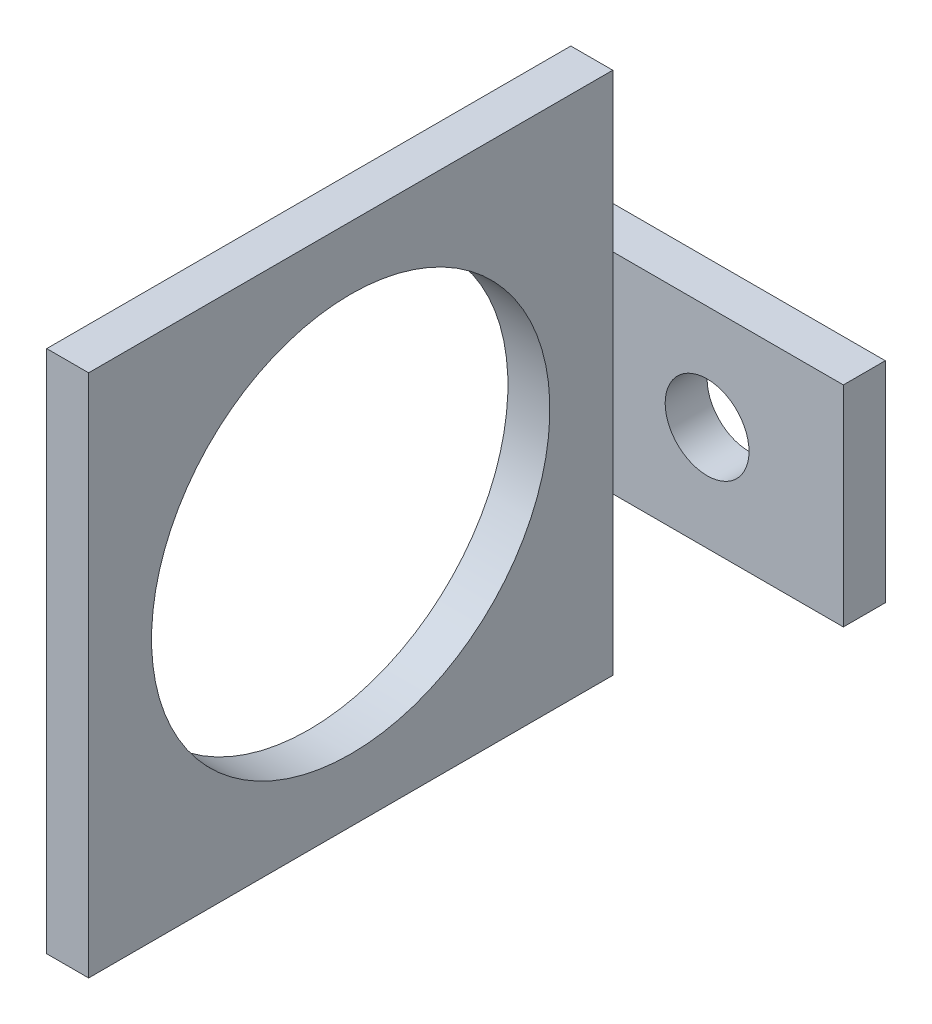
SolidWorks part; units mm, degrees
ref_plane "Front Plane" through (0, 0, 0) normal (0, 0, 1) x (1, 0, 0)
ref_plane "Top Plane" through (0, 0, 0) normal (0, 1, 0) x (1, 0, 0)
ref_plane "Right Plane" through (0, 0, 0) normal (1, 0, 0) x (0, 0, -1)
sketch "Sketch1" plane through (0, 0, 0) normal (0, 0, 1) x (1, 0, 0)
  line L1 (-6.5, 5) -> (6.5, 5)
  line L2 (-6.5, 5) -> (-6.5, -5)
  line L3 (-6.5, -5) -> (6.5, -5)
  line L4 (6.5, 5) -> (6.5, -5)
  line L5 (-6.5, 5) -> (6.5, -5) construction
  line L6 (-6.5, -5) -> (6.5, 5) construction
  point P0 (0, 0)
  dimension "D1" = 13
  dimension "D2" = 10
extrude "Boss-Extrude1" add sketch "Sketch1" along normal blind 2
sketch "Sketch2" plane through (0, 0, 2) normal (0, 0, 1) x (1, 0, 0)
  line L0 (-6.5, -5) -> (6.5, -5) construction
  line L1 (-6.5, 5) -> (-4.5, 5)
  line L2 (-6.5, 5) -> (-6.5, -5)
  line L3 (-6.5, -5) -> (-4.5, -5)
  line L4 (-4.5, 5) -> (-4.5, -5)
  dimension "D1" = 2
extrude "Boss-Extrude2" add sketch "Sketch2" along normal blind 25
sketch "Sketch4" plane through (0, 5, 0) normal (0, 1, 0) x (1, 0, 0)
  line L1 (-6.5, -27) -> (-4.5, -27)
  line L2 (-6.5, -27) -> (-6.5, -2)
  line L3 (-6.5, -2) -> (-4.5, -2)
  line L4 (-4.5, -27) -> (-4.5, -2)
extrude "Boss-Extrude3" add sketch "Sketch4" along normal blind 7.5
sketch "Sketch5" plane through (0, -5, 0) normal (0, -1, 0) x (1, 0, 0)
  line L1 (-6.5, 27) -> (-4.5, 27)
  line L2 (-6.5, 27) -> (-6.5, 2)
  line L3 (-6.5, 2) -> (-4.5, 2)
  line L4 (-4.5, 27) -> (-4.5, 2)
extrude "Boss-Extrude4" add sketch "Sketch5" along normal blind 7.5
sketch "Sketch6" plane through (0, 0, 0) normal (0, 0, -1) x (-1, 0, 0)
  circle A0 centre (0, 0) radius 2
  dimension "D1" = 4
extrude "Cut-Extrude1" cut sketch "Sketch6" against normal blind 7.5
sketch "Sketch7" plane through (-4.5, 0, 0) normal (1, 0, 0) x (0, 0, -1)
  line L0 (-27, -12.5) -> (-27, 12.5) construction
  line L1 (-2, -12.5) -> (-27, -12.5) construction
  circle A0 centre (-14.5, 0) radius 9.5
  dimension "D1" = 19
  dimension "D2" = 12.5
  dimension "D3" = 12.5
extrude "Cut-Extrude2" cut sketch "Sketch7" against normal through all
